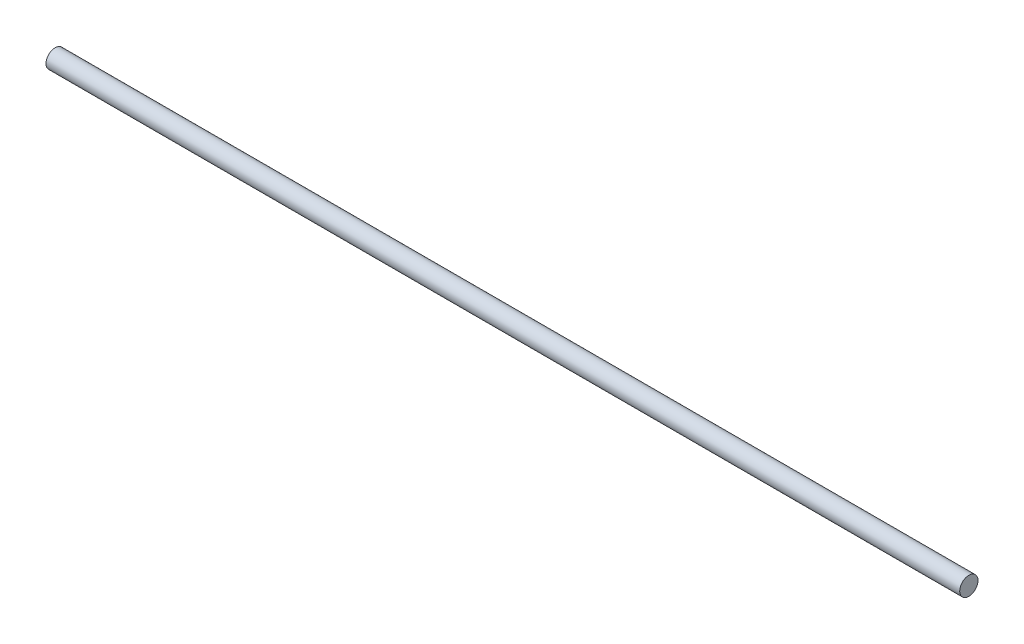
SolidWorks part; units mm, degrees
ref_plane "Front Plane" through (0, 0, 0) normal (0, 0, 1) x (1, 0, 0)
ref_plane "Top Plane" through (0, 0, 0) normal (0, 1, 0) x (1, 0, 0)
ref_plane "Right Plane" through (0, 0, 0) normal (1, 0, 0) x (0, 0, -1)
sketch "Sketch1" plane through (0, 0, 0) normal (1, 0, 0) x (0, 0, -1)
  circle A0 centre (0, 0) radius 1.5
  dimension "D1" = 3
extrude "Boss-Extrude1" add sketch "Sketch1" along normal blind 150
